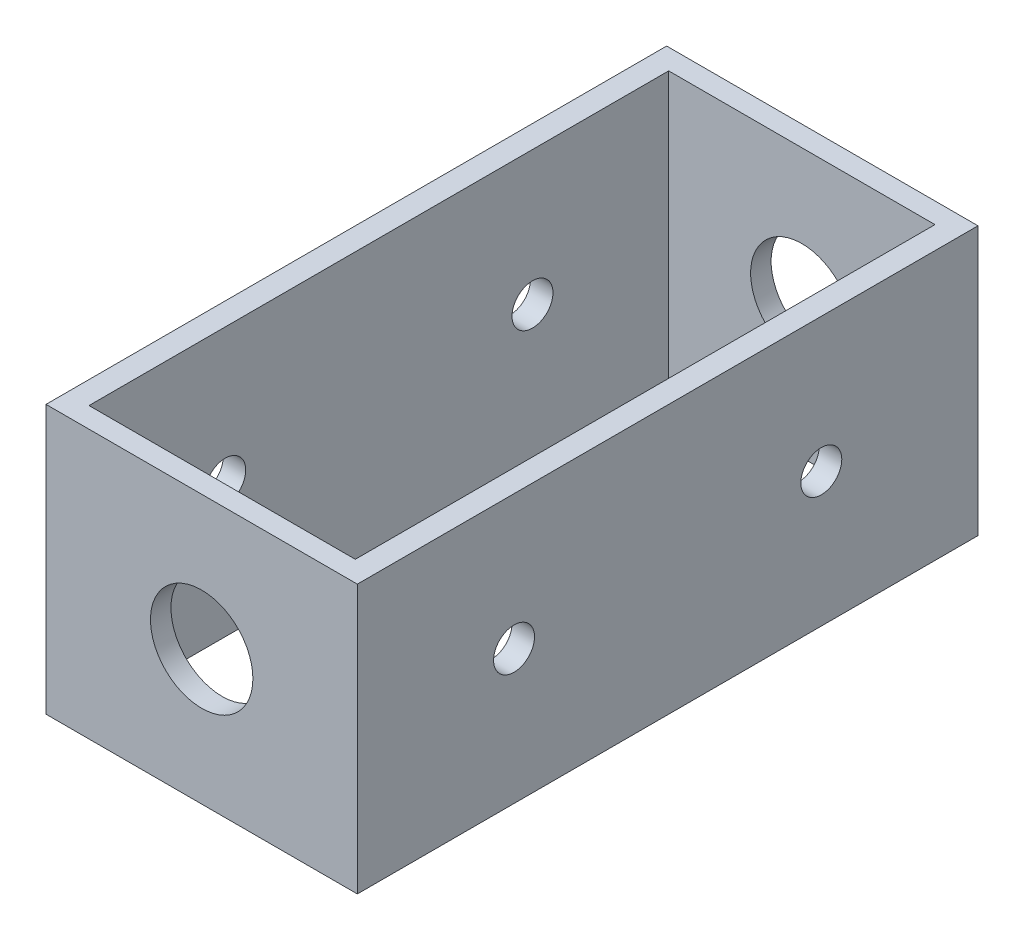
SolidWorks part; units mm, degrees
ref_plane "Front Plane" through (0, 0, 0) normal (0, 0, 1) x (1, 0, 0)
ref_plane "Top Plane" through (0, 0, 0) normal (0, 1, 0) x (1, 0, 0)
ref_plane "Right Plane" through (0, 0, 0) normal (1, 0, 0) x (0, 0, -1)
sketch "Sketch1" plane through (0, 0, 0) normal (0, 1, 0) x (1, 0, 0)
  line L1 (-7.6, -15.15) -> (7.6, -15.15)
  line L2 (-7.6, -15.15) -> (-7.6, 15.15)
  line L3 (-7.6, 15.15) -> (7.6, 15.15)
  line L4 (7.6, -15.15) -> (7.6, 15.15)
  line L5 (-7.6, -15.15) -> (7.6, 15.15) construction
  line L6 (-7.6, 15.15) -> (7.6, -15.15) construction
  line L7 (-6.5, -14.15) -> (6.5, -14.15)
  line L8 (-6.5, -14.15) -> (-6.5, 14.15)
  line L9 (-6.5, 14.15) -> (6.5, 14.15)
  line L10 (6.5, -14.15) -> (6.5, 14.15)
  line L11 (-6.5, -14.15) -> (6.5, 14.15) construction
  line L12 (-6.5, 14.15) -> (6.5, -14.15) construction
  point P0 (0, 0)
  point P6 (0, 0)
  dimension "D1" = 30.3
  dimension "D2" = 15.2
  dimension "D3" = 28.3
  dimension "D4" = 13
extrude "Boss-Extrude1" add sketch "Sketch1" along normal blind 13.1
sketch "Sketch2" plane through (7.6, 0, 0) normal (1, 0, 0) x (0, 0, -1)
  line L0 (-15.15, 13.1) -> (-15.15, 0) construction
  line L1 (-15.15, 13.1) -> (15.15, 13.1) construction
  circle A0 centre (-7.5, 6.55) radius 1
  circle A1 centre (7.5, 6.55) radius 1
  dimension "D1" = 2
  dimension "D2" = 15
  dimension "D3" = 7.65
  dimension "D4" = 6.55
extrude "Cut-Extrude1" cut sketch "Sketch2" against normal through all
sketch "Sketch3" plane through (0, 0, 15.15) normal (0, 0, 1) x (1, 0, 0)
  line L0 (-7.6, 13.1) -> (7.6, 13.1) construction
  line L1 (7.6, 13.1) -> (7.6, 0) construction
  circle A0 centre (0, 6.55) radius 2.5
  dimension "D1" = 5
  dimension "D2" = 6.55
  dimension "D3" = 7.6
extrude "Cut-Extrude2" cut sketch "Sketch3" against normal through all
